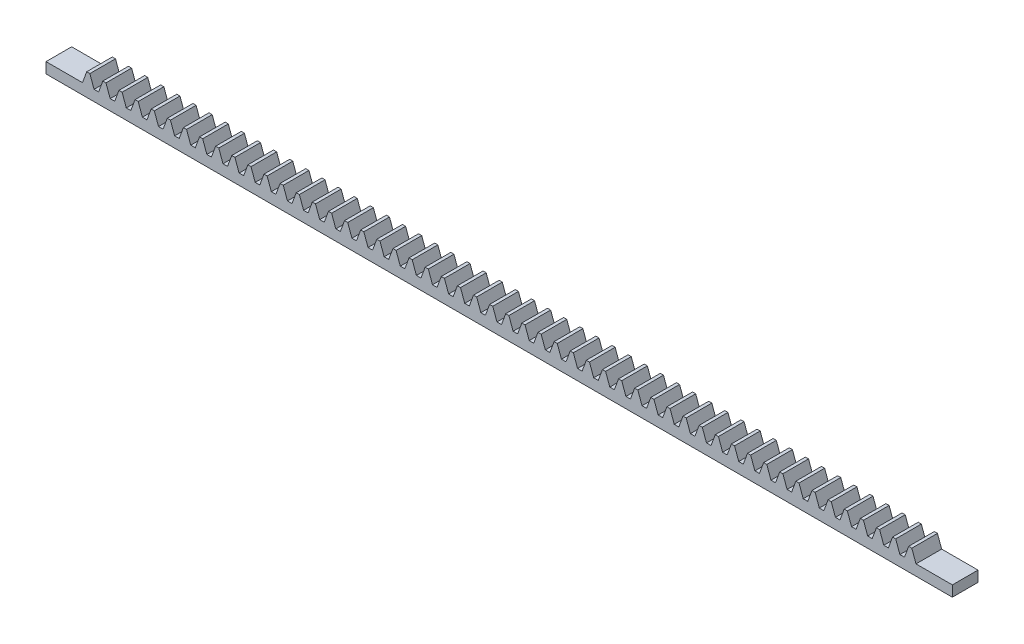
SolidWorks part; units mm, degrees
extrude "Blank" add sketch "BlankSke" against normal blind 4.5
sketch "BlankSke" plane through (0, 0, 0) normal (0, 0, 1) x (1, 0, 0)
  line L1 (0, 0) -> (147, 0)
  line L2 (0, 0) -> (0, 2.9)
  line L3 (0, 2.9) -> (147, 2.9)
  line L4 (147, 0) -> (147, 2.9)
  dimension "Length" = 147
  dimension "Blank_height" = 2.9
ref_plane "Plane1" through (0, 0, 0) normal (0, 0, 1) x (1, 0, 0)
ref_plane "Plane2" through (0, 0, 0) normal (0, 1, 0) x (1, 0, 0)
ref_plane "Plane3" through (0, 0, 0) normal (1, 0, 0) x (0, 0, -1)
other "Configuration Table"
sketch "HoldingSke" plane through (0, 0, 0) normal (0, 1, 0) x (1, 0, 0)
  line L0 (0, 0) -> (0.1546, 1.1003)
  line L1 (-15, 0) -> (100, 0) construction
  line L2 (0, 0) -> (-2.1039, 2.3779)
  line L3 (0, 0) -> (-11.863, 4.5341)
  line L4 (0, 0) -> (5.1973, 6.897)
  line L5 (0, 0) -> (-23.7986, -8.8762)
  line L6 (0, 0) -> (-10.5278, -7.1032)
  line L9 (-71.009, 38.7566) -> (67.1258, 89.0336)
  line L10 (-76.2, 3.2779) -> (-74.2, 3.2779)
  line L11 (0, 0) -> (-4.5, 0)
  line L12 (-76.2, 101.6) -> (-76.166, 101.6)
  line L13 (24.9733, 27.94) -> (52.9518, 28.4284)
  line L14 (24.9733, 27.94) -> (24.9743, 27.94)
  line L15 (24.9733, 27.94) -> (100.4006, 29.5858)
  circle A0 centre (0, 0) radius 19.05
  circle A1 centre (0, 0) radius 1
  circle A2 centre (0, 0) radius 12.7
  dimension "MPH" = 2
  dimension "Diameter" = 38.1
  dimension "Num_teeth" = 53
  dimension "Pitch" = 1.1111
  dimension "Show_teeth" = 998
  dimension "Thickness" = 12.7
  dimension "Ap" = 20
  dimension "Pitch_height" = 2
  dimension "Width" = 4.5
  dimension "Backlash" = 0.034
  dimension "Addendum_fac" = 1
  dimension "Dedendum_fac" = 1.25
  dimension "Clearance_fac" = 0.25
  dimension "Dedendum_add" = 0.001
  dimension "Length" = 147
  dimension "Module" = 0.9
sketch "TooCutSkeIll" plane through (0, 0, 0) normal (0, 0, 1) x (1, 0, 0)
  line L0 (-1.1278, 2.8763) -> (-0.4535, 1.0237)
  line L1 (-0.2411, 0.875) -> (0.2411, 0.875)
  line L2 (0.4535, 1.0237) -> (1.1278, 2.8763)
  line L3 (147, 2.9) -> (0, 2.9) construction
  line L4 (0, 0) -> (0, 64.897) construction
  line L5 (-13.208, 2) -> (12.954, 2) construction
  line L6 (0, 0) -> (147, 0) construction
  line L7 (0.8089, 2) -> (0.8089, 48.7463) construction
  line L8 (-0.8089, 2) -> (-0.8089, 48.7463) construction
  line L9 (1.1616, 2.9) -> (1.1616, 2.9254)
  line L10 (-1.1616, 2.9) -> (-1.1616, 2.9254)
  line L11 (-1.1616, 2.9254) -> (1.1616, 2.9254)
  arc A0 (0.2411, 0.875) -> (0.4535, 1.0237) centre (0.2411, 1.101) ccw
  arc A1 (-0.4535, 1.0237) -> (-0.2411, 0.875) centre (-0.2411, 1.101) ccw
  arc A2 (1.1616, 2.9) -> (1.1278, 2.8763) centre (1.1616, 2.864) ccw
  arc A3 (-1.1278, 2.8763) -> (-1.1616, 2.9) centre (-1.1616, 2.864) ccw
  dimension "Pitch_height" = 2
  dimension "Addendum_plus" = 0.9254
  dimension "Pressure_angle" = 20
  dimension "Gap_width" = 1.6177
  dimension "Dedendum" = 1.125
extrude "ToothCutIll" [suppressed] cut sketch "TooCutSkeIll" against normal through all
sketch "TooCutSkeSim" plane through (0, 0, 0) normal (0, 0, 1) x (1, 0, 0)
  line L0 (0.3994, 0.875) -> (-0.3994, 0.875)
  line L1 (1.1457, 2.9254) -> (0.3994, 0.875)
  line L2 (0, 17.4625) -> (0, 53.467) construction
  line L3 (1.1457, 2.9254) -> (-1.1457, 2.9254)
  line L6 (-1.1457, 2.9254) -> (-0.3994, 0.875)
  line L9 (-0.8089, 2) -> (0.8089, 2) construction
  line L10 (0, 0) -> (147, 0) construction
  line L11 (0.8089, 2) -> (0.8089, 53.467) construction
  line L12 (-0.8089, 2) -> (-0.8089, 53.467) construction
  dimension "Pitch_height" = 2
  dimension "Addendum_plus" = 0.9254
  dimension "Pressure_angle" = 20
  dimension "Gap_width" = 1.6177
  dimension "Dedendum" = 1.125
extrude "ToothCutSim" cut sketch "TooCutSkeSim" against normal through all
pattern_linear "TeethCuts" count 53 spacing 2.8274 along (1, 0, 0) of "ToothCutIll", "ToothCutSim"
sketch "Sketch1" plane through (147, 0, 0) normal (1, 0, 0) x (0, 0, -1)
  line L0 (0, 0) -> (0, 0.875) construction
  line L1 (0, 0.875) -> (4.5, 0.875)
  line L2 (0, 0.875) -> (0, 0)
  line L3 (0, 0) -> (4.5, 0)
  line L4 (4.5, 0.875) -> (4.5, 0)
  line L5 (0, 0.875) -> (4.5, 0.875) construction
  line L6 (4.5, 0) -> (4.5, 0.875) construction
extrude "Boss-Extrude1" add sketch "Sketch1" along normal blind 6
sketch "Sketch2" plane through (0, 0, 0) normal (-1, 0, 0) x (0, 0, 1)
  line L1 (-4.5, 0.875) -> (0, 0.875)
  line L2 (-4.5, 0.875) -> (-4.5, 0)
  line L3 (-4.5, 0) -> (0, 0)
  line L4 (0, 0.875) -> (0, 0)
extrude "Boss-Extrude2" add sketch "Sketch2" along normal blind 6
sketch "Sketch3" plane through (0, 0, 0) normal (0, -1, 0) x (1, 0, 0)
  line L0 (-6, -4.5) -> (-6, 0) construction
  line L1 (-6, 0) -> (153, 0)
  line L2 (-6, 0) -> (-6, -4.5)
  line L3 (-6, -4.5) -> (153, -4.5)
  line L4 (153, 0) -> (153, -4.5)
extrude "Boss-Extrude3" add sketch "Sketch3" along normal blind 1
equation "' \"Module@HoldingSke\" = 6.35"
equation "' \"Num_teeth@HoldingSke\" = 12"
equation "' \"Ap@HoldingSke\" =  20"
equation "' \"Ap@HoldingSke\" = 20"
equation "' \"Width@HoldingSke\" = 0.25 * 25.4"
equation "' \"Show_teeth@HoldingSke\" = 500"
equation "' \"Backlash@HoldingSke\" = 0.009 * 25.4"
equation "' \"Addendum_fac@HoldingSke\" = 1.0"
equation "' \"Dedendum_fac@HoldingSke\" = 1.25"
equation "' \"Dedendum_add@HoldingSke\" = 0.00005 * 25.4"
equation "' \"Clearance_fac@HoldingSke\" = 0.25"
equation "' \"Pitch_height@HoldingSke\" = 1 * 25.4"
equation "' \"Length@HoldingSke\" = 4.71 * 25.4"
equation "\"Pitch@HoldingSke\" = 1 / \"Module@HoldingSke\""
equation "\"MPH@HoldingSke\" = \"Dedendum_fac@HoldingSke\" / \"Pitch@HoldingSke\" + 2 * \"Dedendum_add@HoldingSke\" + 0.002 * 25.4"
equation "\"MPH@HoldingSke\" = ((sgn( \"MPH@HoldingSke\" - \"Pitch_height@HoldingSke\")+1)*( \"MPH@HoldingSke\" - \"Pitch_height@HoldingSke\"))/2 + \"Pitch_height@HoldingSke\""
equation "\"Blank_height@BlankSke\" = \"Pitch_height@HoldingSke\" + \"Addendum_fac@HoldingSke\"  / \"Pitch@HoldingSke\" "
equation "\"Length@BlankSke\" =  \"Length@HoldingSke\""
equation "\"Face_width@Blank\" = \"Width@HoldingSke\""
equation "\"Pressure_angle@TooCutSkeIll\" = \"Ap@HoldingSke\""
equation "\"Addendum_plus@TooCutSkeIll\" =  \"Addendum_fac@HoldingSke\"  / \"Pitch@HoldingSke\" + 0.001 *25.4"
equation "\"Dedendum@TooCutSkeIll\" = \"Dedendum_fac@HoldingSke\"  / \"Pitch@HoldingSke\""
equation "\"Pitch_height@TooCutSkeIll\" =  \"MPH@HoldingSke\""
equation "\"Gap_width@TooCutSkeIll\" = 3.14159265 / 2 / \"Pitch@HoldingSke\" + 6 * \"Backlash@HoldingSke\""
equation "\"Pressure_angle@TooCutSkeSim\" = \"Ap@HoldingSke\""
equation "\"Addendum_plus@TooCutSkeSim\" =  \"Addendum_fac@HoldingSke\"  / \"Pitch@HoldingSke\" + 0.001 * 25.4"
equation "\"Dedendum@TooCutSkeSim\" = \"Dedendum_fac@HoldingSke\"  / \"Pitch@HoldingSke\""
equation "\"Pitch_height@TooCutSkeSim\" =  \"MPH@HoldingSke\""
equation "\"Gap_width@TooCutSkeSim\" = 3.14159265 / 2 / \"Pitch@HoldingSke\" + 6 * \"Backlash@HoldingSke\""
equation "\"Root_fillet@TooCutSkeIll\" = \"Clearance_fac@HoldingSke\" / \"Pitch@HoldingSke\" + \"Dedendum_add@HoldingSke\""
equation "\"Break_rad@TooCutSkeIll\" = 0.02 / \"Pitch@HoldingSke\" * 2"
equation "\"Linear_pitch@TeethCuts\" = 3.14159265 / \"Pitch@HoldingSke\""
equation "\"Num_teeth@HoldingSke\" = int( ( \"Length@HoldingSke\" + 0 ) / (3.14159265 / \"Pitch@HoldingSke\")) + 0.9999  + 1"
equation " \"Num_teeth@TeethCuts\" = int( \"Show_teeth@HoldingSke\" ) + 1"
equation " \"Num_teeth@TeethCuts\" = ((sgn( \"Num_teeth@TeethCuts\" - \"Num_teeth@HoldingSke\" )-1)*( \"Num_teeth@TeethCuts\" - \"Num_teeth@HoldingSke\" ))/-2+ \"Num_teeth@HoldingSke\""
equation " \"Num_teeth@TeethCuts\" = ((sgn( \"Num_teeth@TeethCuts\" - 2.0)+1)*( \"Num_teeth@TeethCuts\" - 2.0))/2 +2.0"
